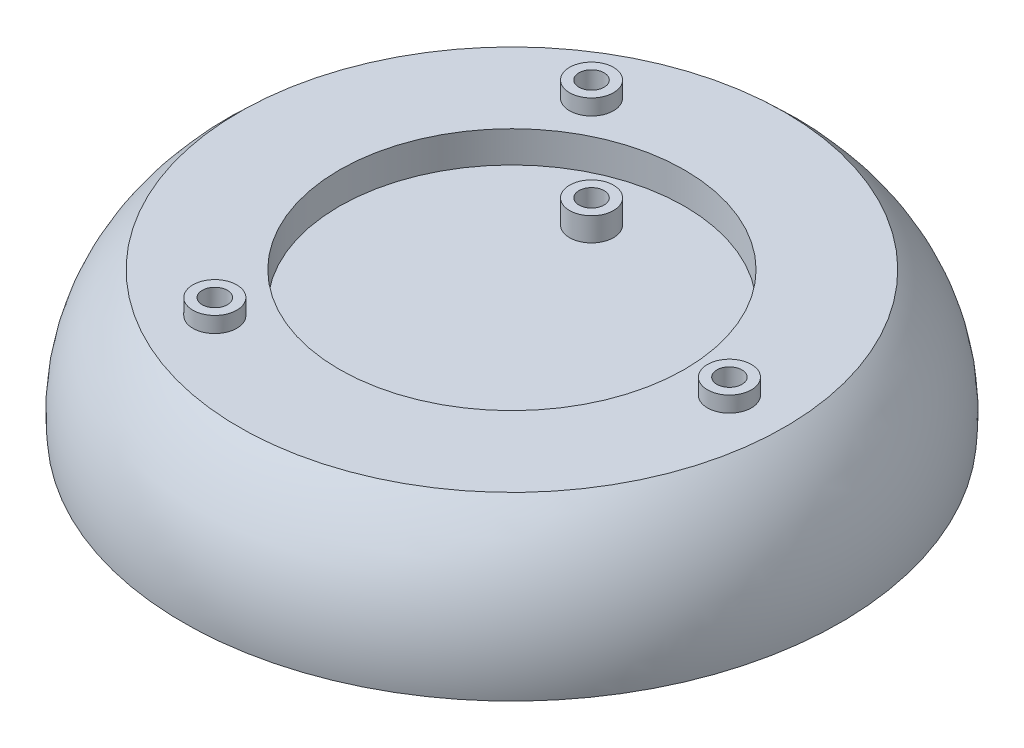
SolidWorks part; units mm, degrees
ref_plane "Front Plane" through (0, 0, 0) normal (0, 0, 1) x (1, 0, 0)
ref_plane "Top Plane" through (0, 0, 0) normal (0, 1, 0) x (1, 0, 0)
ref_plane "Right Plane" through (0, 0, 0) normal (1, 0, 0) x (0, 0, -1)
sketch "Sketch2" plane through (0, 0, 0) normal (1, 0, 0) x (0, 0, -1)
  line L0 (0, 0) -> (0, 3973.9037) construction
  line L1 (0, 0) -> (-100, 0)
  line L3 (-85, 35) -> (-55, 35)
  arc A0 (-100, 0) -> (-85, 35) centre (-53.1296, 0.627) cw
  point P3 (0, 0)
  point P4 (0, 0)
  point P10 (-55, 35)
  dimension "D1" = 100
  dimension "D2" = 35
  dimension "D3" = 30
  dimension "D4" = 55
revolve "Revolve-Thin7" add sketch "Sketch2" angle 360 about L0
sketch "Sketch4" plane through (0, 5, 0) normal (0, 1, 0) x (1, 0, 0)
  line L0 (69.282, 0) -> (-34.641, 60) construction
  line L1 (-34.641, 60) -> (-34.641, -60) construction
  line L2 (-34.641, -60) -> (69.282, 0) construction
  circle A0 centre (0, 0) radius 69.282 construction
  circle A1 centre (69.282, 0) radius 4
  circle A2 centre (-34.641, 60) radius 4
  circle A3 centre (-34.641, -60) radius 4
  dimension "D1" = 8
  dimension "D2" = 8
  dimension "D3" = 8
extrude "Cut-Extrude1" cut sketch "Sketch4" along normal up to surface (35 mm away) up to face at (0, 40, -86.9044)
sketch "Sketch5" plane through (0, 5, 0) normal (0, 1, 0) x (1, 0, 0)
  circle A0 centre (-34.641, 60) radius 7
  circle A1 centre (-34.641, -60) radius 4
  circle A2 centre (-34.641, -60) radius 4
  circle A3 centre (-34.641, 60) radius 4
  circle A4 centre (-34.641, 60) radius 4
  circle A5 centre (69.282, 0) radius 4
  circle A6 centre (69.282, 0) radius 4
  circle A8 centre (-34.641, -60) radius 7
  circle A9 centre (69.282, 0) radius 7
  dimension "D4" = 3
  dimension "D5" = 3
  dimension "D6" = 3
  dimension "D1" = 0
  dimension "D2" = 0
  dimension "D3" = 0
extrude "Boss-Extrude1" add sketch "Sketch5" along normal blind 7.5
sketch "Sketch6" plane through (0, 40, 0) normal (0, 1, 0) x (1, 0, 0)
  circle A0 centre (-34.641, 60) radius 7 construction
  circle A1 centre (0, 0) radius 86.9044
  circle A2 centre (0, 0) radius 86.9044
  circle A3 centre (-34.641, -60) radius 7
  circle A4 centre (-34.641, -60) radius 7
  circle A5 centre (-34.641, -60) radius 7 construction
  circle A6 centre (69.282, 0) radius 7 construction
  circle A7 centre (-34.641, 60) radius 7
  circle A8 centre (-34.641, -60) radius 7
  circle A9 centre (69.282, 0) radius 7
  circle A10 centre (69.282, 0) radius 4 construction
  circle A11 centre (-34.641, 60) radius 4 construction
  circle A12 centre (-34.641, -60) radius 4 construction
  circle A13 centre (69.282, 0) radius 4
  circle A14 centre (-34.641, 60) radius 4
  circle A15 centre (-34.641, -60) radius 4
  dimension "D1" = 0
  dimension "D2" = 0
extrude "Boss-Extrude3" add sketch "Sketch6" along normal blind 5 contours A15 | A4 | A9 | A13 | A7 | A14
